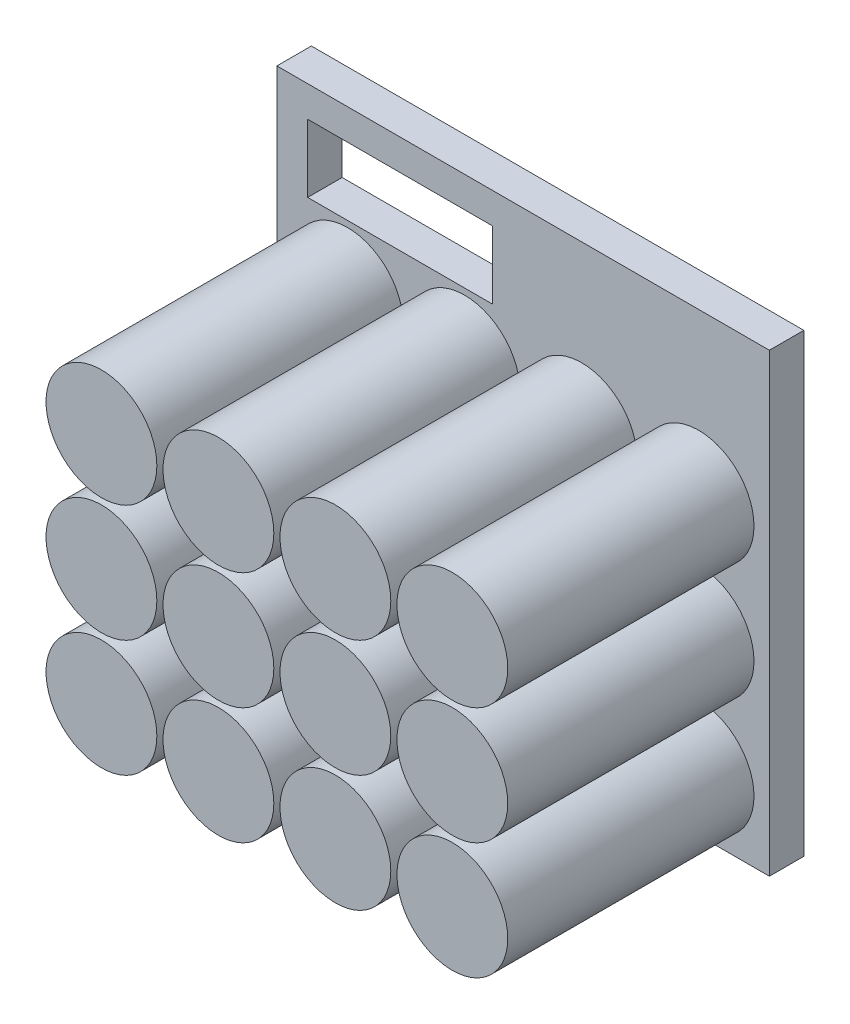
SolidWorks part; units mm, degrees
ref_plane "前视基准面" through (0, 0, 0) normal (0, 0, 1) x (1, 0, 0)
ref_plane "上视基准面" through (0, 0, 0) normal (0, 1, 0) x (1, 0, 0)
ref_plane "右视基准面" through (0, 0, 0) normal (1, 0, 0) x (0, 0, -1)
sketch "草图1" plane through (0, 0, 0) normal (0, 0, 1) x (1, 0, 0)
  line L1 (-35.0249, 13.6567) -> (44.9751, 13.6567)
  line L2 (-35.0249, 13.6567) -> (-35.0249, -60.3433)
  line L3 (-35.0249, -60.3433) -> (44.9751, -60.3433)
  line L4 (44.9751, 13.6567) -> (44.9751, -60.3433)
  line L5 (-30.0249, 8.6567) -> (-0.0249, 8.6567)
  line L6 (-30.0249, 8.6567) -> (-30.0249, -2.3433)
  line L7 (-30.0249, -2.3433) -> (-0.0249, -2.3433)
  line L8 (-0.0249, 8.6567) -> (-0.0249, -2.3433)
  dimension "D1" = 80
  dimension "D2" = 74
  dimension "D3" = 5
  dimension "D4" = 5
  dimension "D5" = 30
  dimension "D6" = 11
extrude "凸台-拉伸1" add sketch "草图1" against normal blind 5.6 contours L2 L1 L4 L3
sketch "草图2" plane through (0, 0, 0) normal (0, 0, 1) x (1, 0, 0)
  line L4 (-35.0249, 13.6567) -> (-35.0249, -60.3433)
  line L5 (-35.0249, -60.3433) -> (44.9751, -60.3433)
  line L6 (44.9751, -60.3433) -> (44.9751, 13.6567)
  line L7 (44.9751, 13.6567) -> (-35.0249, 13.6567)
  line L8 (-35.0249, 13.6567) -> (-35.0249, -60.3433)
  line L9 (-35.0249, -60.3433) -> (44.9751, -60.3433)
  line L10 (44.9751, -60.3433) -> (44.9751, 13.6567)
  line L11 (44.9751, 13.6567) -> (-35.0249, 13.6567)
  circle A0 centre (-23.5249, -50.3433) radius 9
  circle A1 centre (-4.5249, -50.3433) radius 9
  circle A2 centre (14.4751, -50.3433) radius 9
  circle A3 centre (33.4751, -50.3433) radius 9
  circle A4 centre (-4.5249, -31.3433) radius 9
  circle A5 centre (14.4751, -31.3433) radius 9
  circle A6 centre (33.4751, -31.3433) radius 9
  circle A7 centre (-4.5249, -12.3433) radius 9
  circle A8 centre (14.4751, -12.3433) radius 9
  circle A9 centre (33.4751, -12.3433) radius 9
  circle A10 centre (-23.5249, -31.3433) radius 9
  circle A11 centre (-23.5249, -12.3433) radius 9
  dimension "D2" = 18
  dimension "D3" = 11.5
  dimension "D4" = 10
  dimension "D1" = 0
  dimension "D5" = 4
  dimension "D6" = 3
extrude "凸台-拉伸2" add sketch "草图2" along normal blind 40 contours A0 | A10 | A11 | A7 | A4 | A1 | A2 | A5 | A8 | A9 | A6 | A3 | L8 L9 L10 L11
